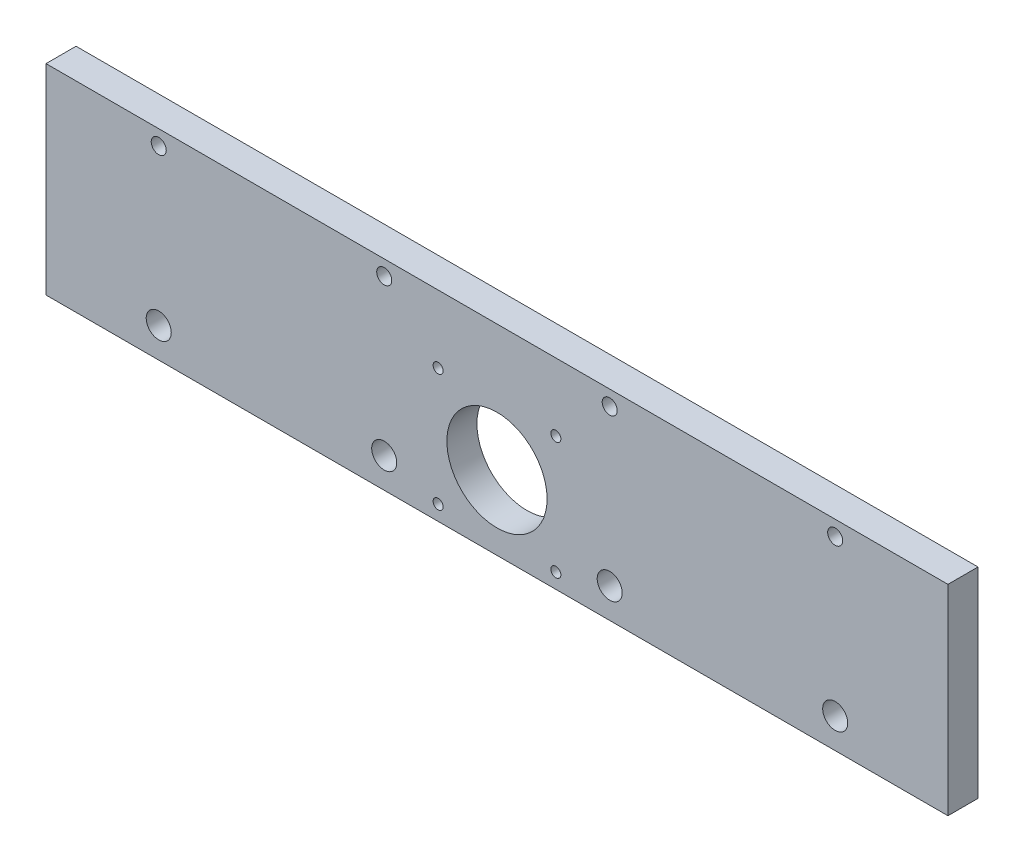
SolidWorks part; units mm, degrees
material "HDPE-green"
ref_plane "Front Plane" through (0, 0, 0) normal (0, 0, 1) x (1, 0, 0)
ref_plane "Top Plane" through (0, 0, 0) normal (0, 1, 0) x (1, 0, 0)
ref_plane "Right Plane" through (0, 0, 0) normal (1, 0, 0) x (0, 0, -1)
sketch "Sketch1" plane through (0, 0, 0) normal (0, 0, 1) x (1, 0, 0)
  line L1 (-180, -40) -> (180, -40)
  line L2 (-180, -40) -> (-180, 40)
  line L3 (-180, 40) -> (180, 40)
  line L4 (180, -40) -> (180, 40)
  line L5 (-180, -40) -> (180, 40) construction
  line L6 (-180, 40) -> (180, -40) construction
  point P0 (0, 0)
extrude "Boss-Extrude1" add sketch "Sketch1" along normal blind 12
sketch "Sketch2" plane through (0, 0, 12) normal (0, 0, 1) x (1, 0, 0)
  line L0 (180, -40) -> (180, 40) construction
  line L1 (180, 40) -> (-180, 40) construction
  line L2 (-180, -40) -> (180, -40) construction
  circle A0 centre (135, 34) radius 3
  circle A1 centre (135, -28) radius 5
  dimension "D1" = 6
  dimension "D2" = 45
  dimension "D3" = 6
  dimension "D4" = 10
  dimension "D5" = 12
extrude "Cut-Extrude1" cut sketch "Sketch2" against normal up to next
pattern_linear "LPattern1" count 4 spacing 90 along (-1, 0, 0) of "Cut-Extrude1"
sketch "Sketch3" plane through (0, 0, 12) normal (0, 0, 1) x (1, 0, 0)
  line L0 (-180, -40) -> (180, -40) construction
  circle A0 centre (0, -10.5) radius 20
  dimension "D1" = 40
  dimension "D2" = 29.5
extrude "Cut-Extrude2" cut sketch "Sketch3" against normal up to next
sketch "Sketch4" plane through (0, 0, 12) normal (0, 0, 1) x (1, 0, 0)
  line L0 (0, 17.4189) -> (0, -17.4926) construction
  line L1 (-17.6695, 0) -> (16.7711, 0) construction
  circle A0 centre (-23.5, 13) radius 2
  circle A1 centre (0, -10.5) radius 20 construction
  circle A2 centre (-23.5, -34) radius 2
  dimension "D1" = 4
  dimension "D2" = 23.5
  dimension "D3" = 23.5
  dimension "D4" = 4
  dimension "D5" = 23.5
  dimension "D6" = 23.5
extrude "Cut-Extrude3" cut sketch "Sketch4" against normal up to next
mirror "Mirror2" about plane through (0, 0, 0) normal (1, 0, 0) of "Cut-Extrude3"
